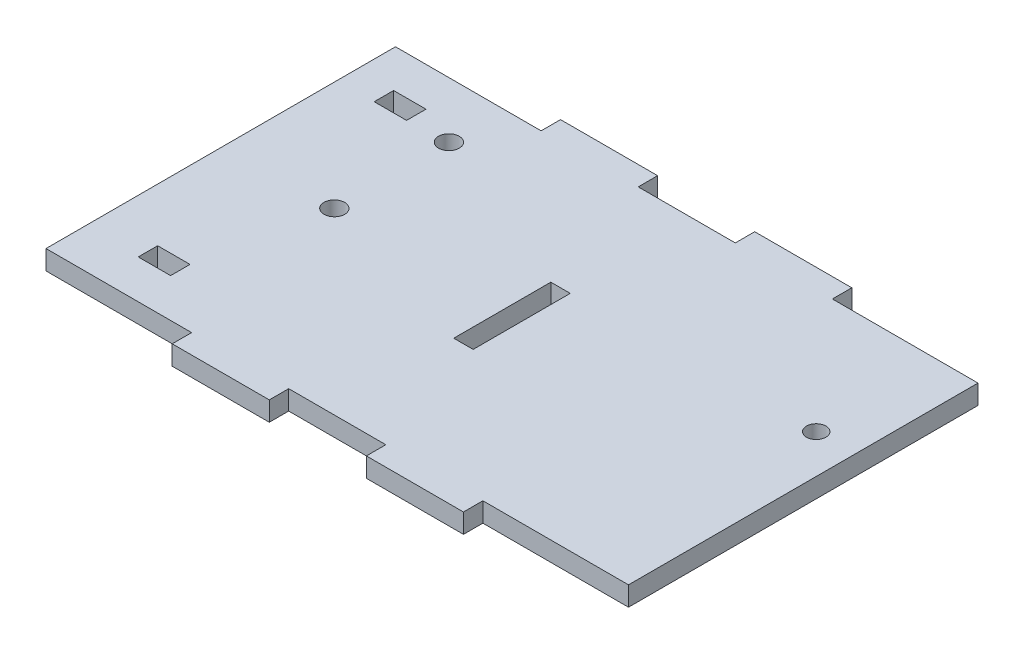
SolidWorks part; units mm, degrees
material "ABS PC"
ref_plane "Front Plane" through (0, 0, 0) normal (0, 0, 1) x (1, 0, 0)
ref_plane "Top Plane" through (0, 0, 0) normal (0, 1, 0) x (1, 0, 0)
ref_plane "Right Plane" through (0, 0, 0) normal (1, 0, 0) x (0, 0, -1)
sketch "Sketch1" plane through (0, 0, 0) normal (0, 1, 0) x (1, 0, 0)
  line L0 (-45, 27) -> (-22.5, 27)
  line L1 (-22.5, 27) -> (-22.5, 30)
  line L2 (-22.5, 30) -> (-7.5, 30)
  line L3 (-7.5, 30) -> (-7.5, 27)
  line L4 (-7.5, 27) -> (7.5, 27)
  line L5 (7.5, 27) -> (7.5, 30)
  line L6 (7.5, 30) -> (22.5, 30)
  line L7 (22.5, 30) -> (22.5, 27)
  line L8 (22.5, 27) -> (45, 27)
  line L9 (45, 27) -> (45, -27)
  line L10 (45, -27) -> (22.5, -27)
  line L11 (22.5, -27) -> (22.5, -30)
  line L12 (22.5, -30) -> (7.5, -30)
  line L13 (7.5, -30) -> (7.5, -27)
  line L14 (7.5, -27) -> (-7.5, -27)
  line L15 (-7.5, -27) -> (-7.5, -30)
  line L16 (-7.5, -30) -> (-22.5, -30)
  line L17 (-22.5, -30) -> (-22.5, -27)
  line L18 (-22.5, -27) -> (-45, -27)
  line L19 (-45, -27) -> (-45, 27)
  line L20 (-45, 0) -> (0, 0) construction
  line L21 (0, 0) -> (45, 0) construction
  dimension "D1" = 90
  dimension "D2" = 3
  dimension "D3" = 15
  dimension "D4" = 60
extrude "Boss-Extrude1" add sketch "Sketch1" along normal blind 3
sketch "Sketch2" plane through (0, 3, 0) normal (0, 1, 0) x (1, 0, 0)
  circle A0 centre (-31.75, 19.05) radius 1.5
  circle A1 centre (-31.75, -8.89) radius 1.5
  circle A2 centre (20.32, 24.13) radius 1.5
  circle A3 centre (19.05, -24.13) radius 1.5
  dimension "D1" = 3
extrude "Cut-Extrude1" [suppressed] cut sketch "Sketch2" against normal through all
sketch "Sketch3" plane through (0, 3, 0) normal (0, 1, 0) x (1, 0, 0)
  line L0 (-31.75, -25.146) -> (-31.75, -13.7795) construction
  line L1 (-36.75, -18) -> (-31.75, -18)
  line L2 (-36.75, -18) -> (-36.75, -21)
  line L3 (-36.75, -21) -> (-31.75, -21)
  line L4 (-31.75, -18) -> (-31.75, -21)
  line L6 (-34.29, -11.176) -> (-34.29, 21.59) construction
  line L7 (-34.29, 18) -> (-39.29, 18)
  line L8 (-34.29, 18) -> (-34.29, 21)
  line L9 (-34.29, 21) -> (-39.29, 21)
  line L10 (-39.29, 18) -> (-39.29, 21)
  line L11 (-39.29, 21) -> (-39.29, 27) construction
  line L12 (-22.5, 27) -> (-45, 27) construction
  line L13 (-36.75, -21) -> (-36.75, -27) construction
  line L14 (-45, -27) -> (-22.5, -27) construction
  dimension "D1" = 3
  dimension "D3" = 5
  dimension "D4" = 6
extrude "Cut-Extrude2" cut sketch "Sketch3" against normal through all
sketch "Sketch4" plane through (0, 3, 0) normal (0, 1, 0) x (1, 0, 0)
  line L0 (0, 7.5) -> (0, 0) construction
  line L1 (-1.5, 7.5) -> (1.5, 7.5)
  line L2 (-1.5, 7.5) -> (-1.5, -7.5)
  line L3 (-1.5, -7.5) -> (1.5, -7.5)
  line L4 (1.5, 7.5) -> (1.5, -7.5)
  line L5 (0, 0) -> (0, -7.5) construction
  dimension "D1" = 3
  dimension "D2" = 15
extrude "Cut-Extrude3" cut sketch "Sketch4" against normal through all
sketch "Sketch5" plane through (0, 3, 0) normal (0, 1, 0) x (1, 0, 0)
  line L0 (39, 8) -> (39, 27) construction
  line L1 (35, 27) -> (42.2414, 27) construction
  line L2 (39, 8) -> (45, 8) construction
  line L3 (45, -27) -> (45, 27) construction
  circle A0 centre (39, 8) radius 1.5
  dimension "D1" = 3
  dimension "D2" = 6
  dimension "D3" = 19
extrude "Cut-Extrude4" cut sketch "Sketch5" against normal through all
sketch "Sketch6" plane through (0, 3, 0) normal (0, 1, 0) x (1, 0, 0)
  circle A0 centre (-28.1, 18.35) radius 1.6
  circle A1 centre (-28.1, 0.65) radius 1.6
  circle A2 centre (-28.1, 18.35) radius 1.6 construction
  circle A3 centre (-28.1, 0.65) radius 1.6 construction
extrude "Cut-Extrude5" cut sketch "Sketch6" against normal through all
